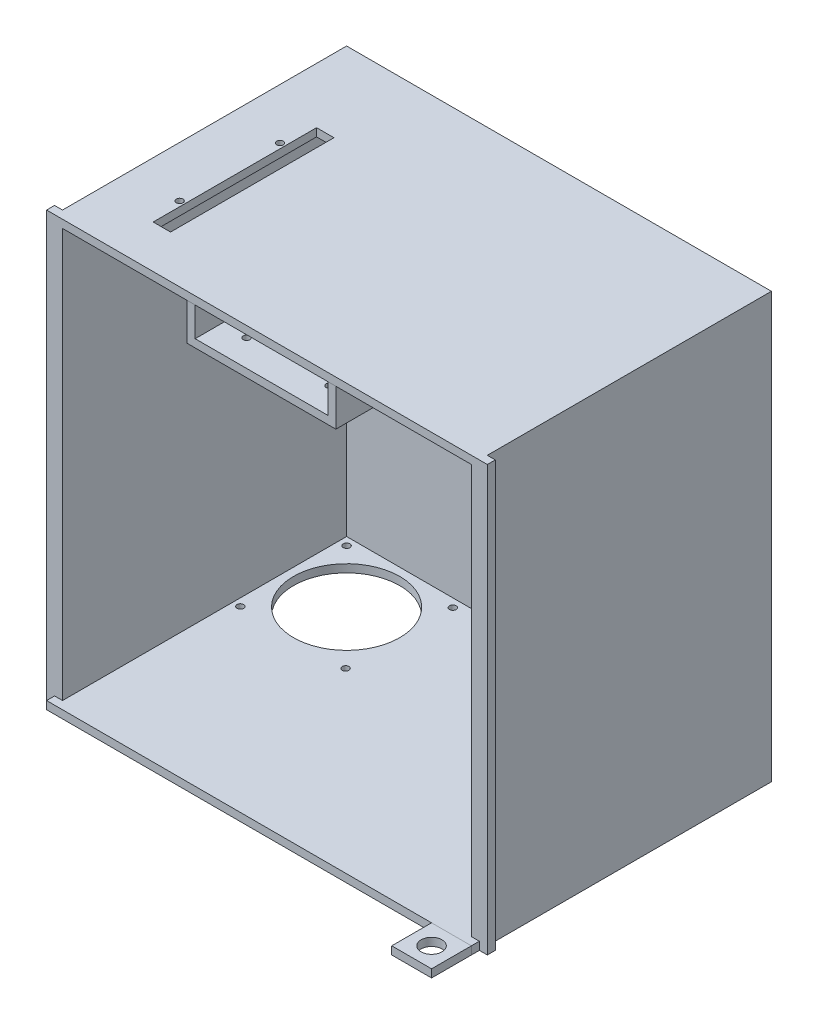
SolidWorks part; units mm, degrees
ref_plane "Front Plane" through (0, 0, 0) normal (0, 0, 1) x (1, 0, 0)
ref_plane "Top Plane" through (0, 0, 0) normal (0, 1, 0) x (1, 0, 0)
ref_plane "Right Plane" through (0, 0, 0) normal (1, 0, 0) x (0, 0, -1)
sketch "Sketch1" plane through (0, 0, 0) normal (0, 0, 1) x (1, 0, 0)
  line L2 (-101.6, 101.6) -> (101.6, 101.6)
  line L3 (-101.6, 101.6) -> (-101.6, -101.6)
  line L4 (-101.6, -101.6) -> (101.6, -101.6)
  line L5 (101.6, 101.6) -> (101.6, -101.6)
  line L6 (-101.6, 101.6) -> (101.6, -101.6) construction
  line L7 (-101.6, -101.6) -> (101.6, 101.6) construction
  point P2 (0, 0)
  dimension "D1" = 203.2
  dimension "D2" = 203.2
extrude "Outter Box" add sketch "Sketch1" along normal blind 139.7
shell "Shell1" thickness 3.81
sketch "Sketch4" plane through (0, 97.79, 0) normal (0, -1, 0) x (1, 0, 0)
  line L0 (97.79, 139.7) -> (-97.79, 139.7) construction
  line L1 (-38.1558, 76.2) -> (32.9642, 76.2)
  line L2 (-38.1558, 76.2) -> (-38.1558, 139.7)
  line L3 (-38.1558, 139.7) -> (32.9642, 139.7)
  line L4 (32.9642, 76.2) -> (32.9642, 139.7)
  line L5 (-38.1558, 76.2) -> (32.9642, 139.7) construction
  line L6 (-38.1558, 139.7) -> (32.9642, 76.2) construction
  point P0 (-2.5958, 107.95)
  dimension "D1" = 71.12
  dimension "D2" = 63.5
extrude "RFID Card holder" add sketch "Sketch4" along normal blind 17.78 separate body contours L2 L1 L4 L3
shell "Shell2" thickness 3.81
sketch "Sketch5" plane through (0, -101.6, 0) normal (0, -1, 0) x (1, 0, 0)
  line L0 (-101.6, 0) -> (101.6, 0) construction
  line L1 (-101.6, 139.7) -> (-101.6, 0) construction
  circle A0 centre (-68.58, 33.02) radius 25.4
  dimension "D1" = 50.8
  dimension "D2" = 33.02
  dimension "D3" = 33.02
sketch "Sketch6" plane through (0, 0, 139.7) normal (0, 0, 1) x (1, 0, 0)
  line L0 (101.6, -101.6) -> (101.6, 101.6) construction
  line L1 (-101.6, -101.6) -> (101.6, -101.6)
  line L2 (-101.6, -101.6) -> (-101.6, -97.79)
  line L3 (-101.6, -97.79) -> (101.6, -97.79)
  line L4 (101.6, -101.6) -> (101.6, -97.79)
extrude "Boss-Extrude4" add sketch "Sketch6" along normal blind 3.81 separate body
sketch "Sketch12" plane through (0, 101.6, 0) normal (0, 1, 0) x (1, 0, 0)
  line L1 (-66.6324, -119.182) -> (-74.9509, -119.182)
  line L2 (-66.6324, -119.182) -> (-66.6324, -41.0135)
  line L3 (-66.6324, -41.0135) -> (-74.9509, -41.0135)
  line L4 (-74.9509, -119.182) -> (-74.9509, -41.0135)
  dimension "D1" = 8.3185
  dimension "D2" = 78.1685
extrude "Cut-Extrude7" cut sketch "Sketch12" against normal blind 3.81
sketch "Sketch13" plane through (101.6, 0, 0) normal (1, 0, 0) x (0, 0, -1)
  line L0 (-139.7, -101.6) -> (0, -101.6) construction
  line L1 (-139.7, 101.6) -> (-135.89, 101.6)
  line L2 (-139.7, 101.6) -> (-139.7, -101.6)
  line L3 (-139.7, -101.6) -> (-135.89, -101.6)
  line L4 (-135.89, 101.6) -> (-135.89, -101.6)
  dimension "D1" = 3.81
extrude "Boss-Extrude5" add sketch "Sketch13" along normal blind 3.81
sketch "Sketch14" plane through (-101.6, 0, 0) normal (-1, 0, 0) x (0, 0, 1)
  line L0 (143.51, -101.6) -> (0, -101.6) construction
  line L1 (139.7, 101.6) -> (135.89, 101.6)
  line L2 (139.7, 101.6) -> (139.7, -101.6)
  line L3 (139.7, -101.6) -> (135.89, -101.6)
  line L4 (135.89, 101.6) -> (135.89, -101.6)
  dimension "D1" = 3.81
extrude "Boss-Extrude6" add sketch "Sketch14" along normal blind 3.81
sketch "Sketch16" plane through (0, 0, 143.51) normal (0, 0, 1) x (1, 0, 0)
  line L0 (-101.6, -101.6) -> (101.6, -101.6) construction
  line L1 (101.6, -97.79) -> (82.55, -97.79)
  line L2 (101.6, -97.79) -> (101.6, -101.6)
  line L3 (101.6, -101.6) -> (82.55, -101.6)
  line L4 (82.55, -97.79) -> (82.55, -101.6)
  dimension "D1" = 19.05
extrude "Boss-Extrude7" add sketch "Sketch16" along normal blind 19.05 separate body
sketch "Sketch18" plane through (0, -101.6, 0) normal (0, -1, 0) x (1, 0, 0)
  line L0 (82.55, 162.56) -> (101.6, 143.51) construction
  line L1 (82.55, 162.56) -> (101.6, 162.56) construction
  line L2 (82.55, 162.56) -> (82.55, 143.51) construction
  circle A0 centre (92.075, 153.035) radius 5
  dimension "D1" = 10
extrude "Cut-Extrude9" cut sketch "Sketch18" against normal blind 3.81
extrude "Cut-Extrude10" cut sketch "Sketch5" against normal blind 3.81
sketch "Sketch19" plane through (0, 80.01, 0) normal (0, -1, 0) x (1, 0, 0)
  line L0 (-38.1558, 139.7) -> (32.9642, 76.2) construction
  line L1 (-2.5958, 76.2) -> (-2.5958, 127) construction
  line L2 (-38.1558, 76.2) -> (32.9642, 76.2) construction
  line L3 (-2.5958, 127) -> (-22.4395, 127) construction
  line L4 (-2.5958, 127) -> (17.248, 127) construction
  circle A0 centre (-22.4395, 127) radius 1.6
  circle A1 centre (17.248, 127) radius 1.6
  dimension "D4" = 3.2
  dimension "D5" = 3.2
  dimension "D1" = 50.8
  dimension "D2" = 19.8438
  dimension "D3" = 19.8438
extrude "Cut-Extrude11" cut sketch "Sketch19" against normal blind 3.81
sketch "Sketch20" plane through (0, -97.79, 0) normal (0, 1, 0) x (1, 0, 0)
  line L0 (-97.79, -3.81) -> (-97.79, -62.23) construction
  line L1 (-97.79, -139.7) -> (-97.79, -3.81) construction
  line L2 (-97.79, -3.81) -> (-39.37, -3.81) construction
  line L3 (-97.79, -3.81) -> (97.79, -3.81) construction
  line L4 (-97.79, -62.23) -> (-39.37, -62.23) construction
  line L5 (-97.79, -3.81) -> (-93.98, -7.62) construction
  line L6 (-97.79, -62.23) -> (-94.238, -58.1784) construction
  line L7 (-39.37, -62.23) -> (-43.4216, -58.678) construction
  line L8 (-39.37, -3.81) -> (-42.922, -7.8616) construction
  circle A1 centre (-94.238, -58.1784) radius 1.6
  circle A2 centre (-43.4216, -58.678) radius 1.6
  circle A3 centre (-42.922, -7.8616) radius 1.6
  circle A4 centre (-93.98, -7.62) radius 1.6
  dimension "D8" = 3.2
  dimension "D9" = 3.2
  dimension "D10" = 3.2
  dimension "D11" = 3.2
  dimension "D1" = 58.42
  dimension "D2" = 58.42
  dimension "D3" = 58.42
  dimension "D4" = 5.3882
  dimension "D5" = 5.3882
  dimension "D6" = 5.3882
  dimension "D7" = 5.3882
extrude "Cut-Extrude12" cut sketch "Sketch20" against normal blind 3.81
sketch "Sketch21" plane through (0, 0, 3.81) normal (0, 0, 1) x (1, 0, 0)
  line L1 (-1.905, 97.79) -> (1.905, 97.79)
  line L2 (-1.905, 97.79) -> (-1.905, -97.79)
  line L3 (-1.905, -97.79) -> (1.905, -97.79)
  line L4 (1.905, 97.79) -> (1.905, -97.79)
  line L5 (-1.905, 97.79) -> (1.905, -97.79) construction
  line L6 (-1.905, -97.79) -> (1.905, 97.79) construction
  point P0 (0, 0)
  dimension "D1" = 195.58
  dimension "D2" = 3.81
extrude "Boss-Extrude9" add sketch "Sketch21" along normal blind 12.7
sketch "Sketch23" plane through (0, 97.79, 0) normal (0, -1, 0) x (1, 0, 0)
  line L0 (-74.9509, 119.182) -> (-74.9509, 119.6583) construction
  line L1 (-74.9509, 41.0135) -> (-74.9509, 40.5373) construction
  line L2 (-74.9509, 119.6583) -> (-74.9509, 104.1008) construction
  line L3 (-74.9509, 41.0135) -> (-74.9509, 119.182) construction
  line L4 (-74.9509, 40.5373) -> (-74.9509, 56.0948) construction
  line L5 (-74.9509, 56.0948) -> (-77.3321, 56.0948) construction
  line L6 (-74.9509, 104.1008) -> (-77.3321, 104.1008) construction
  circle A0 centre (-77.3321, 56.0948) radius 1.5875
  circle A1 centre (-77.3321, 104.1008) radius 1.5875
  dimension "D6" = 3.175
  dimension "D8" = 3.175
  dimension "D1" = 0.4762
  dimension "D2" = 0.4762
  dimension "D3" = 15.5575
  dimension "D4" = 15.5575
  dimension "D5" = 2.3813
  dimension "D7" = 2.3813
extrude "Cut-Extrude13" cut sketch "Sketch23" against normal blind 3.81
